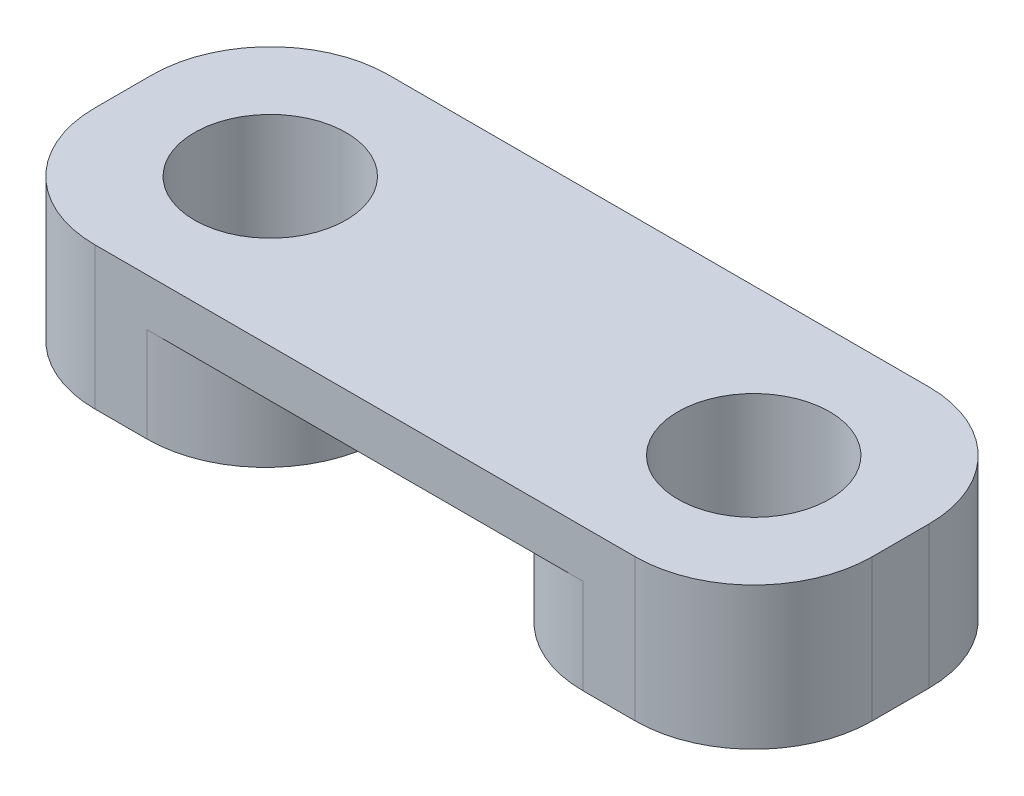
SolidWorks part; units mm, degrees
ref_plane "Front Plane" through (0, 0, 0) normal (0, 0, 1) x (1, 0, 0)
ref_plane "Top Plane" through (0, 0, 0) normal (0, 1, 0) x (1, 0, 0)
ref_plane "Right Plane" through (0, 0, 0) normal (1, 0, 0) x (0, 0, -1)
sketch "Sketch1" plane through (0, 0, 0) normal (0, 1, 0) x (1, 0, 0)
  line L0 (-8.199, 0) -> (8.199, 0)
  line L1 (8.199, 0) -> (8.199, 6.2)
  line L2 (8.199, 6.2) -> (-8.199, 6.2)
  line L3 (-8.199, 6.2) -> (-8.199, 0)
  line L4 (0, 0) -> (0, 9.4869) construction
  circle A0 centre (-5.099, 3.1) radius 1.6
  circle A1 centre (5.099, 3.1) radius 1.6
  point P3 (0, 0)
  point P9 (0, 0)
  point P11 (0, 0)
  point P12 (-8.199, 3.1)
  dimension "D1" = 3.2
  dimension "D2" = 6.2
  dimension "D3" = 5.099
  dimension "D4" = 16.398
extrude "Boss-Extrude1" add sketch "Sketch1" along normal blind 3
sketch "Sketch5" plane through (0, 0, 0) normal (0, 0, 1) x (1, 0, 0)
  line L0 (-2.099, 0) -> (-2.099, 2)
  line L1 (-8.199, 0) -> (8.199, 0) construction
  line L2 (-2.099, 2) -> (2.099, 2)
  line L3 (2.099, 2) -> (2.099, 0)
  line L4 (-8.199, 3) -> (8.199, 3) construction
  line L8 (-2.099, 0) -> (2.099, 0)
  point P8 (0, 0)
  dimension "D1" = 1
  dimension "D2" = 4.198
extrude "Cut-Extrude4" cut sketch "Sketch5" against normal through all
fillet "Fillet2" radius 2.5 8 edges at (8.199, 1.5, -6.2) (8.199, 1.5, 0) (-8.199, 1.5, -6.2) (-8.199, 1.5, 0) (2.099, 1, 0) (2.099, 1, -6.2) (-2.099, 1, -6.2) (-2.099, 1, 0)
equation "\"D3@Sketch1\"=10.198039/2"
